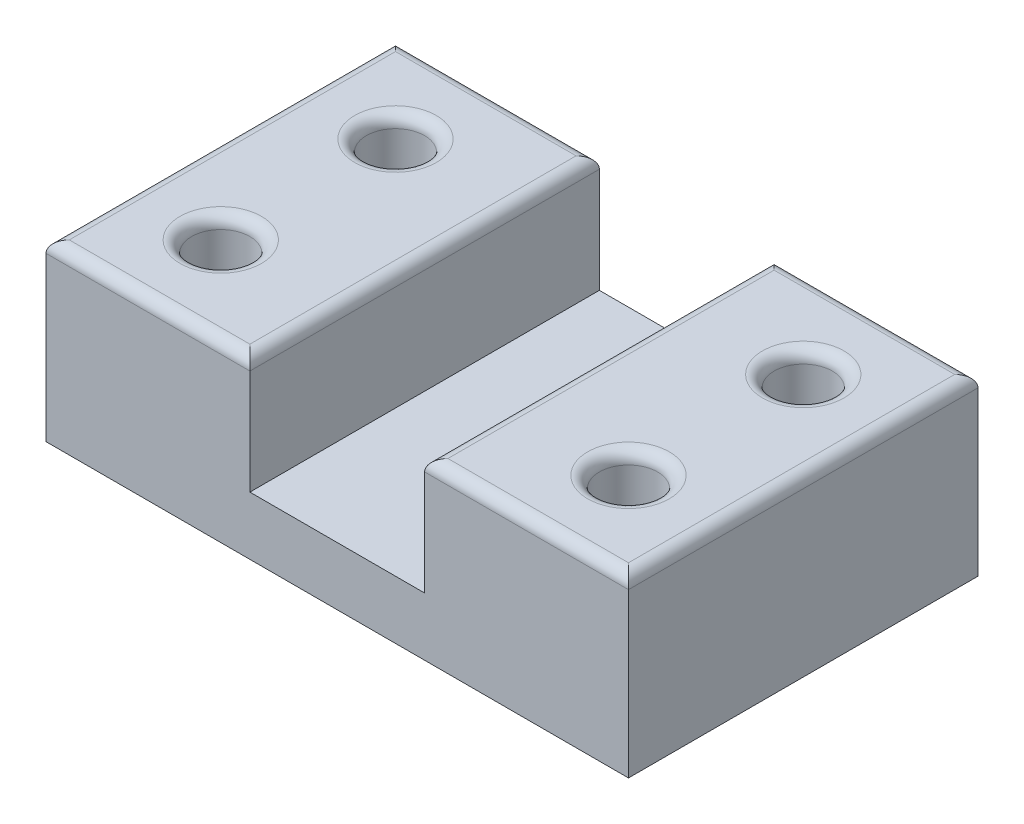
SolidWorks part; units mm, degrees
ref_plane "Front Plane" through (0, 0, 0) normal (0, 0, 1) x (1, 0, 0)
ref_plane "Top Plane" through (0, 0, 0) normal (0, 1, 0) x (1, 0, 0)
ref_plane "Right Plane" through (0, 0, 0) normal (1, 0, 0) x (0, 0, -1)
sketch "Sketch1" plane through (0, 0, 0) normal (0, 0, 1) x (1, 0, 0)
  line L0 (-56.708, -12.7) -> (70.292, -12.7)
  line L1 (70.292, -12.7) -> (70.292, 25.4)
  line L2 (70.292, 25.4) -> (25.842, 25.4)
  line L3 (25.842, 25.4) -> (25.842, 0)
  line L4 (25.842, 0) -> (-12.258, 0)
  line L5 (-12.258, 0) -> (-12.258, 25.4)
  line L6 (-12.258, 25.4) -> (-56.708, 25.4)
  line L7 (-56.708, 25.4) -> (-56.708, -12.7)
  dimension "D1" = 127
  dimension "D2" = 38.1
  dimension "D3" = 44.45
  dimension "D4" = 38.1
  dimension "D5" = 38.1
  dimension "D6" = 12.7
extrude "Boss-Extrude1" add sketch "Sketch1" along normal blind 76.2 contours L7 L0 L1 L2 L3 L4 L5 L6
sketch "Sketch2" plane through (0, 25.4, 0) normal (0, 1, 0) x (1, 0, 0)
  line L0 (-56.708, -76.2) -> (-56.708, 0) construction
  line L1 (-12.258, 0) -> (-56.708, 0) construction
  line L2 (-12.258, -76.2) -> (-56.708, -76.2) construction
  line L3 (70.292, -76.2) -> (70.292, 0) construction
  circle A0 centre (-37.658, -19.05) radius 6.35
  circle A4 centre (-37.658, -57.15) radius 6.35
  circle A5 centre (51.242, -19.05) radius 6.35
  circle A6 centre (51.242, -57.15) radius 6.35
  point P6 (50.5728, -19.05)
  point P10 (0, 0)
  point P11 (0, 0)
  point P14 (0, 0)
  point P15 (-37.658, -58.8773)
  point P21 (51.242, -57.15)
  point P22 (0, 0)
  dimension "D1" = 12.7
  dimension "D4" = 19.05
  dimension "D5" = 19.05
  dimension "D2" = 19.05
  dimension "D3" = 19.05
extrude "Cut-Extrude1" cut sketch "Sketch2" against normal through all
fillet "Fillet1" radius 2.54 12 edges at (70.292, 25.4, 38.1) (48.067, 25.4, 76.2) (25.842, 25.4, 38.1) (48.067, 25.4, 0) (44.892, 25.4, 57.15) (44.892, 25.4, 19.05) (-12.258, 25.4, 38.1) (-34.483, 25.4, 76.2) (-56.708, 25.4, 38.1) (-34.483, 25.4, 0) (-44.008, 25.4, 19.05) (-44.008, 25.4, 57.15)
